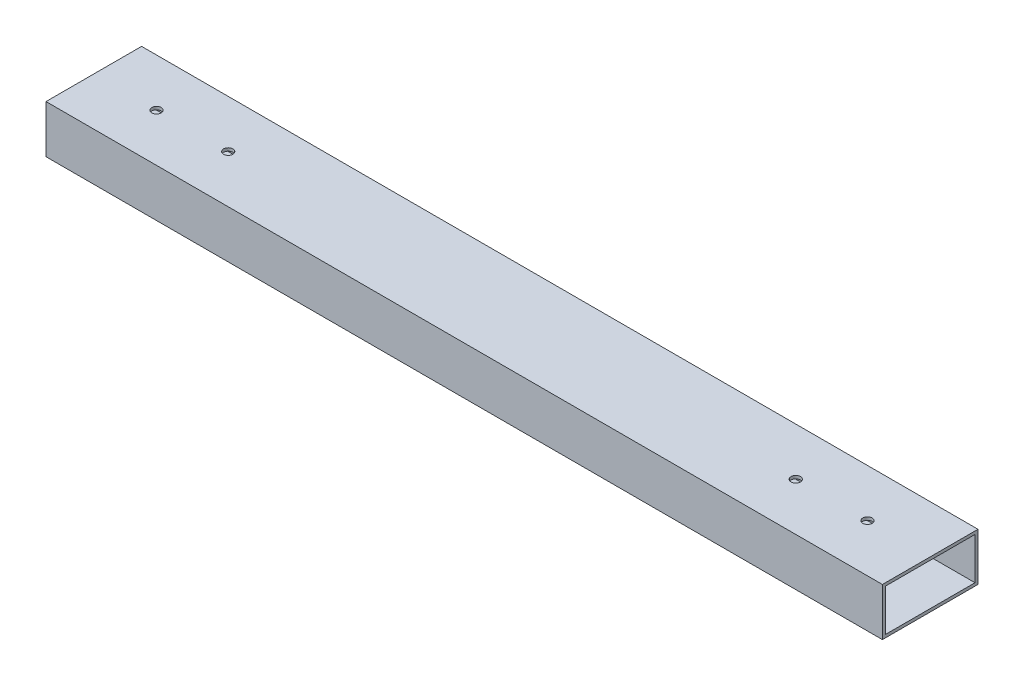
SolidWorks part; units mm, degrees
material "6061-T6 (SS)"
ref_plane "Front Plane" through (0, 0, 0) normal (0, 0, 1) x (1, 0, 0)
ref_plane "Top Plane" through (0, 0, 0) normal (0, 1, 0) x (1, 0, 0)
ref_plane "Right Plane" through (0, 0, 0) normal (1, 0, 0) x (0, 0, -1)
ref_plane "Plane1" through (0, 101.6, 0) normal (0, -1, 0) x (-1, 0, 0)
sketch "Sketch2" plane through (0, 0, 0) normal (1, 0, 0) x (0, 0, -1)
  line L0 (241.3, 127) -> (190.5, 127) construction
  line L1 (190.5, 101.6) -> (190.5, 127) construction
  line L2 (241.3, 101.6) -> (190.5, 101.6) construction
  line L3 (241.3, 101.6) -> (241.3, 127) construction
  line L4 (241.3, 127) -> (190.5, 127)
  line L5 (190.5, 101.6) -> (190.5, 127)
  line L6 (241.3, 101.6) -> (190.5, 101.6)
  line L7 (241.3, 101.6) -> (241.3, 127)
  line L8 (239.7125, 125.4125) -> (192.0875, 125.4125)
  line L9 (192.0875, 103.1875) -> (192.0875, 125.4125)
  line L10 (239.7125, 103.1875) -> (192.0875, 103.1875)
  line L11 (239.7125, 103.1875) -> (239.7125, 125.4125)
  dimension "D1" = 1.5875
extrude "Boss-Extrude1" add sketch "Sketch2" along normal up to vertex (222.25 mm away) and the other way up to vertex (222.25 mm away)
sketch "Sketch4" plane through (0, 0, 0) normal (0, 1, 0) x (1, 0, 0)
  circle A0 centre (150.8125, 215.9) radius 2.4892 construction
  circle A1 centre (188.9125, 215.9) radius 2.4892 construction
  circle A2 centre (150.8125, 215.9) radius 2.4892
  circle A3 centre (188.9125, 215.9) radius 2.4892
extrude "Cut-Extrude2" cut sketch "Sketch4" along normal through all
mirror "Mirror2" about plane through (0, 0, 0) normal (1, 0, 0) of "Cut-Extrude2"
